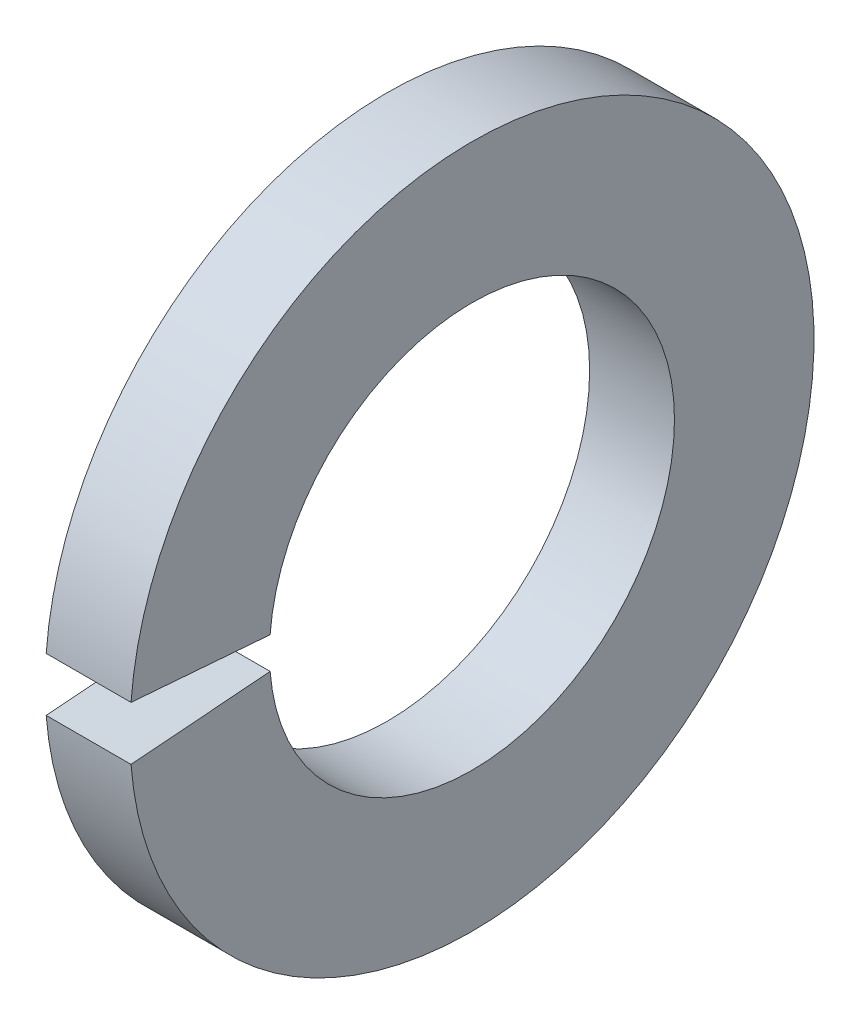
SolidWorks part; units mm, degrees
material "Chrome Stainless Steel"
ref_plane "Front Plane" through (0, 0, 0) normal (0, 0, 1) x (1, 0, 0)
ref_plane "Top Plane" through (0, 0, 0) normal (0, 1, 0) x (1, 0, 0)
ref_plane "Right Plane" through (0, 0, 0) normal (1, 0, 0) x (0, 0, -1)
ref_plane "Plane1" through (0, 0, 0) normal (0, 0.9969, 0.0785) x (-1, 0, 0)
sketch "Sketch1" plane through (0, 0, 0) normal (0, 0.9969, 0.0785) x (-1, 0, 0)
  line L0 (0.7874, 3.175) -> (0, 3.175)
  line L1 (0, 3.175) -> (0, 1.8796)
  line L2 (0, 1.8796) -> (0.7874, 1.8796)
  line L3 (0.7874, 1.8796) -> (0.7874, 3.175)
  line L4 (0, 0) -> (0.7874, 0) construction
revolve "Revolve1" add sketch "Sketch1" angle 351 about L4
